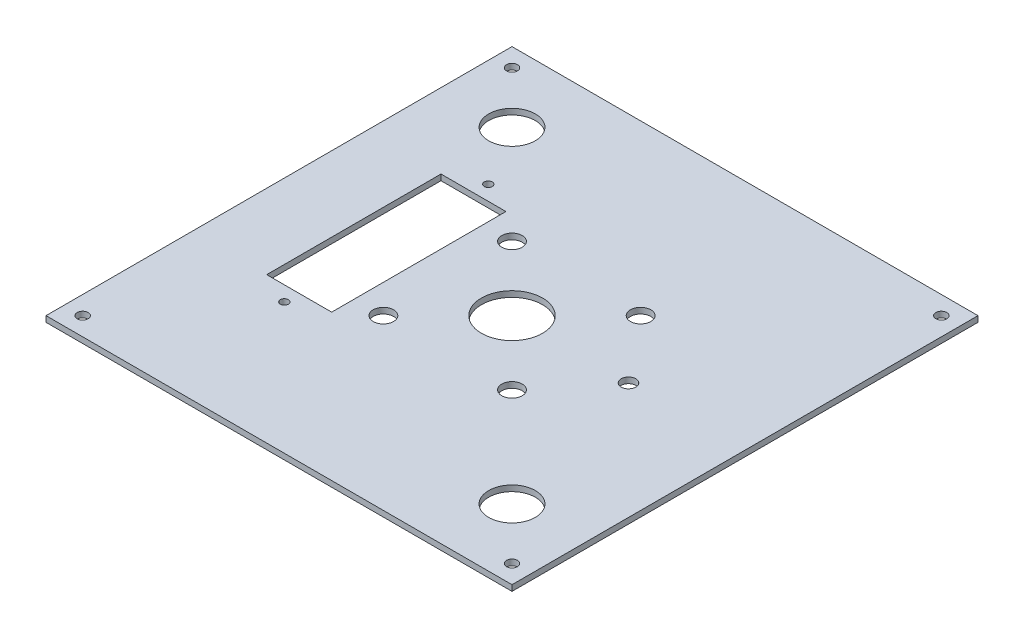
SolidWorks part; units mm, degrees
material "6061-T6 (SS)"
ref_plane "Front Plane" through (0, 0, 0) normal (0, 0, 1) x (1, 0, 0)
ref_plane "Top Plane" through (0, 0, 0) normal (0, 1, 0) x (1, 0, 0)
ref_plane "Right Plane" through (0, 0, 0) normal (1, 0, 0) x (0, 0, -1)
sketch "Sketch1" plane through (0, 0, 0) normal (0, 1, 0) x (1, 0, 0)
  line L1 (-127, -127) -> (127, -127)
  line L2 (-127, -127) -> (-127, 127)
  line L3 (-127, 127) -> (127, 127)
  line L4 (127, -127) -> (127, 127)
  line L5 (-127, -127) -> (127, 127) construction
  line L6 (-127, 127) -> (127, -127) construction
  point P0 (0, 0)
  dimension "D1" = 254
  dimension "D2" = 254
extrude "Boss-Extrude1" add sketch "Sketch1" along normal blind 3.175
sketch "Sketch5" plane through (0, 3.175, 0) normal (0, 1, 0) x (1, 0, 0)
  line L0 (72.7295, -109.6327) -> (-72.7295, 109.6327) construction
  line L1 (101.6, -101.6) -> (-101.6, -101.6) construction
  line L2 (101.6, -101.6) -> (101.6, 101.6) construction
  line L3 (101.6, 101.6) -> (-101.6, 101.6) construction
  line L4 (-101.6, -101.6) -> (-101.6, 101.6) construction
  line L5 (71.842, -71.842) -> (69.597, -69.597) construction
  line L6 (-211.9943, 0) -> (211.9943, 0) construction
  line L7 (0, -149.1838) -> (0, 149.1838) construction
  line L8 (69.0651, 104.109) -> (-69.0651, -104.109) construction
  line L9 (-50.8, -47.498) -> (-50.8, 47.498)
  line L10 (-47.498, -47.498) -> (47.498, -47.498) construction
  line L11 (-47.498, -47.498) -> (-47.498, 47.498) construction
  line L12 (-47.498, 47.498) -> (47.498, 47.498) construction
  line L13 (47.498, -47.498) -> (47.498, 47.498) construction
  line L14 (-47.498, -47.498) -> (47.498, 47.498) construction
  line L15 (-47.498, 47.498) -> (47.498, -47.498) construction
  line L16 (-50.8, 47.498) -> (-86.2057, 47.498)
  line L17 (-86.2057, 47.498) -> (-86.2057, -47.498)
  line L18 (-50.8, -47.498) -> (-86.2057, -47.498)
  circle A0 centre (0, 0) radius 101.6 construction
  circle A1 centre (0, 0) radius 98.425 construction
  point P13 (0, 0)
  point P16 (0, 0)
  point P20 (0, 0)
  point P22 (0, 0)
  point P29 (-50.8, 0)
  dimension "D1" = 203.2
  dimension "D2" = 196.85
  dimension "D3" = 203.2
  dimension "D4" = 203.2
  dimension "D5" = 33.56
  dimension "D6" = 33.56
  dimension "D7" = 94.996
  dimension "D8" = 94.996
  dimension "D9" = 50.8
  dimension "D10" = 94.996
extrude "Cut-Extrude4" cut sketch "Sketch5" against normal blind 25.4
sketch "Sketch2" plane through (0, 3.175, 0) normal (0, 1, 0) x (1, 0, 0)
  line L0 (-127, 127) -> (-127, -127) construction
  line L1 (127, 127) -> (-127, 127) construction
  circle A1 centre (-117, 117) radius 2.9769
  circle A2 centre (117, 117) radius 2.9769
  circle A3 centre (117, -117) radius 2.9769
  circle A4 centre (-117, -117) radius 2.9769
  point P18 (0, 0)
  dimension "D4" = 5.9538
  dimension "D2" = 10
  dimension "D3" = 10
  dimension "D5" = 4
extrude "Cut-Extrude1" cut sketch "Sketch2" against normal blind 3.175
sketch "Sketch4" [suppressed] plane through (0, 3.175, 0) normal (0, 1, 0) x (1, 0, 0)
  line L0 (-191.8154, 0) -> (191.8154, 0) construction
  line L1 (-101.6, -101.6) -> (101.6, -101.6) construction
  line L2 (-101.6, -101.6) -> (-101.6, 101.6) construction
  line L3 (-101.6, 101.6) -> (101.6, 101.6) construction
  line L4 (101.6, -101.6) -> (101.6, 101.6) construction
  line L5 (-101.6, -101.6) -> (101.6, 101.6) construction
  line L6 (-101.6, 101.6) -> (101.6, -101.6) construction
  line L7 (0, -157.3396) -> (0, 157.3396) construction
  circle A0 centre (-91.6, 91.6) radius 2.5
  point P0 (0, 0)
  point P12 (0, 0)
  point P14 (0, 0)
  dimension "D3" = 5
  dimension "D1" = 203.2
  dimension "D2" = 203.2
  dimension "D4" = 10
sketch "Sketch3" plane through (0, 3.175, 0) normal (0, 1, 0) x (1, 0, 0)
  line L0 (-208.9778, 0) -> (208.9778, 0) construction
  line L1 (0, 160.8755) -> (0, -160.8755) construction
  circle A0 centre (-35.052, 35.052) radius 5.5563
  circle A1 centre (35.052, 35.052) radius 5.5562
  circle A2 centre (35.052, -35.052) radius 5.5562
  circle A3 centre (-35.052, -35.052) radius 5.5563
  point P5 (0, 0)
  point P9 (0, 0)
  dimension "D3" = 11.1125
  dimension "D1" = 35.052
  dimension "D2" = 35.052
extrude "Cut-Extrude3" cut sketch "Sketch3" against normal blind 3.175
sketch "Sketch6" plane through (0, 3.175, 0) normal (0, 1, 0) x (1, 0, 0)
  line L0 (-221.1232, 0) -> (221.1232, 0) construction
  line L1 (0, -178.0026) -> (0, 178.0026) construction
  line L2 (-144.8612, -144.8612) -> (144.8612, 144.8612) construction
  line L3 (144.8612, -144.8612) -> (-144.8612, 144.8612) construction
  line L4 (127, 107) -> (107, 107) construction
  line L5 (-127, 107) -> (-107, 107) construction
  line L6 (-127, 107) -> (-127, 127) construction
  line L7 (-127, 127) -> (-107, 127) construction
  line L8 (-107, 107) -> (-107, 127) construction
  line L9 (-127, 107) -> (-107, 127) construction
  line L10 (-127, 127) -> (-107, 107) construction
  line L11 (127, 107) -> (127, 127) construction
  line L12 (127, 127) -> (107, 127) construction
  line L13 (107, 107) -> (107, 127) construction
  line L14 (-127, 127) -> (-127, -127) construction
  circle A0 centre (0, 0) radius 101.6 construction
  circle A1 centre (-88.9, 88.9) radius 12.7
  circle A2 centre (88.9, -88.9) radius 12.7
  point P4 (-117, 117)
  point P5 (0, 0)
  point P9 (0, 0)
  point P12 (0, 0)
  point P15 (0, 0)
  dimension "D1" = 203.2
  dimension "D2" = 25.4
  dimension "D3" = 38.1
extrude "Cut-Extrude5" cut sketch "Sketch6" against normal blind 3.175
sketch "Sketch7" plane through (0, 3.175, 0) normal (0, 1, 0) x (1, 0, 0)
  circle A0 centre (0, 0) radius 16.6687
  dimension "D1" = 33.3375
extrude "Cut-Extrude6" cut sketch "Sketch7" against normal blind 508
sketch "Sketch8" plane through (0, 3.175, 0) normal (0, 1, 0) x (1, 0, 0)
  line L0 (159.2021, 0) -> (-159.2021, 0) construction
  line L1 (-68.5028, -141.0016) -> (-68.5028, 141.0016) construction
  circle A0 centre (-68.5028, 55.5625) radius 2.1844
  circle A1 centre (-68.5028, -55.5625) radius 2.1844
  point P5 (0, 0)
  point P9 (-68.5028, 0)
  dimension "D2" = 4.3688
  dimension "D1" = 55.5625
extrude "Cut-Extrude7" cut sketch "Sketch8" against normal blind 3.175
sketch "Sketch9" plane through (0, 3.175, 0) normal (0, 1, 0) x (1, 0, 0)
  line L0 (-205.0506, 0) -> (205.0506, 0) construction
  line L1 (-47.498, -47.498) -> (47.498, -47.498) construction
  line L2 (-47.498, -47.498) -> (-47.498, 47.498) construction
  line L3 (-47.498, 47.498) -> (47.498, 47.498) construction
  line L4 (47.498, -47.498) -> (47.498, 47.498) construction
  line L5 (-47.498, -47.498) -> (47.498, 47.498) construction
  line L6 (-47.498, 47.498) -> (47.498, -47.498) construction
  line L7 (0, -147.8182) -> (0, 147.8182) construction
  circle A0 centre (0, 0) radius 98.425 construction
  circle A1 centre (63.5, 0) radius 3.9687
  point P10 (0, 0)
  point P13 (0, 0)
  dimension "D1" = 196.85
  dimension "D5" = 7.9375
  dimension "D2" = 94.996
  dimension "D3" = 94.996
  dimension "D4" = 63.5
extrude "Cut-Extrude8" cut sketch "Sketch9" against normal blind 3.175
